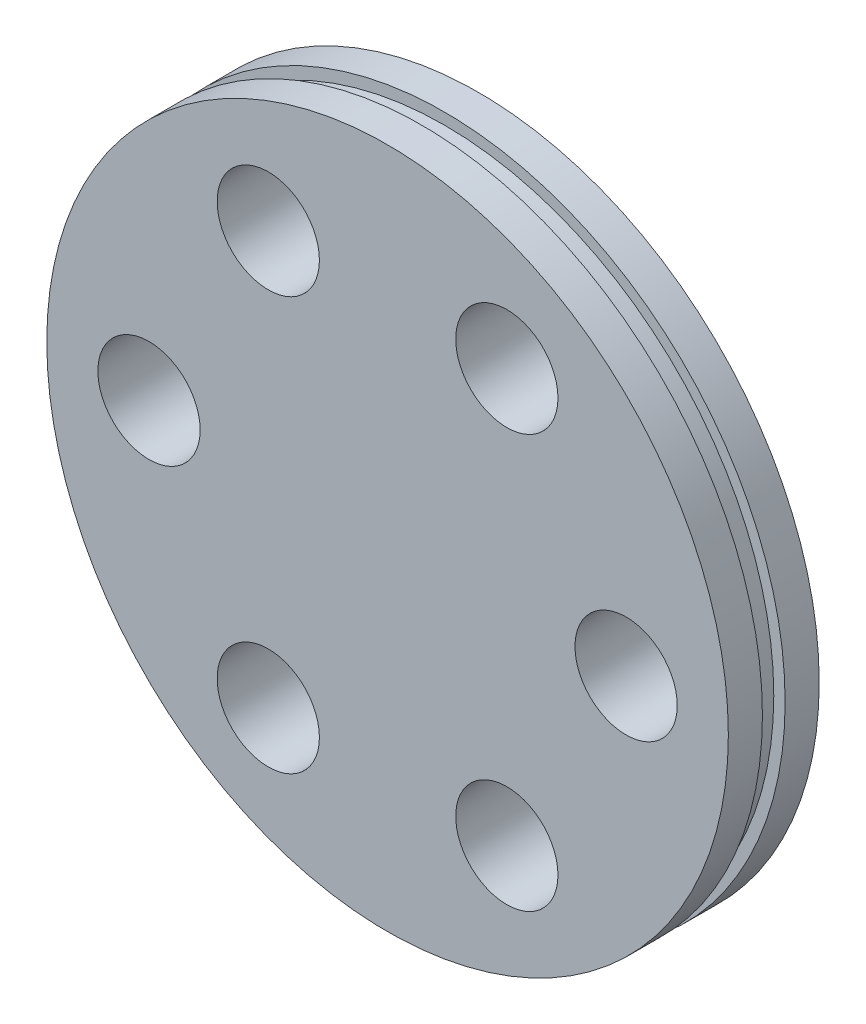
SolidWorks part; units mm, degrees
ref_plane "Plan de face" through (0, 0, 0) normal (0, 0, 1) x (1, 0, 0)
ref_plane "Plan de dessus" through (0, 0, 0) normal (0, 1, 0) x (1, 0, 0)
ref_plane "Plan de droite" through (0, 0, 0) normal (1, 0, 0) x (0, 0, -1)
sketch "Esquisse1" plane through (0, 0, 0) normal (0, 0, 1) x (1, 0, 0)
  line L0 (0, 0) -> (38.8642, 0) construction
  line L1 (0, 0) -> (0, 25.5483) construction
  circle A0 centre (0, 0) radius 11
  circle A1 centre (0, 0) radius 11.5 construction
  circle A3 centre (-16.5, 0) radius 5 construction
  circle A4 centre (0, 0) radius 30
  circle A5 centre (0, 0) radius 22.5 construction
  circle A6 centre (16.5, 0) radius 5 construction
  dimension "D1" = 60
  dimension "D2" = 23
  dimension "D3" = 10
  dimension "D4" = 10
extrude "Boss.-Extru.1" add sketch "Esquisse1" along normal blind 6
sketch "Esquisse2" plane through (0, 0, 6) normal (0, 0, 1) x (1, 0, 0)
  circle A0 centre (0, 0) radius 30
extrude "Boss.-Extru.2" add sketch "Esquisse2" along normal blind 2
ref_plane "Plan1" through (0, 0, 4) normal (0, 0, 1) x (1, 0, 0)
sketch "Esquisse3" plane through (0, 0, 4) normal (0, 0, 1) x (1, 0, 0)
  circle A0 centre (0, 0) radius 30
  circle A1 centre (0, 0) radius 29
  dimension "D1" = 58
  dimension "D2" = 60
extrude "Enlèv. mat.-Extru.1" cut sketch "Esquisse3" against normal blind 1 and the other way blind 1
sketch "Esquisse4" plane through (0, 0, 8) normal (0, 0, 1) x (1, 0, 0)
  circle A0 centre (21, 0) radius 4.5
  circle A1 centre (10.5, 18.1865) radius 4.5
  circle A2 centre (-10.5, 18.1865) radius 4.5
  circle A3 centre (-21, 0) radius 4.5
  circle A4 centre (-10.5, -18.1865) radius 4.5
  circle A5 centre (10.5, -18.1865) radius 4.5
extrude "Ajourage" cut sketch "Esquisse4" against normal through all
